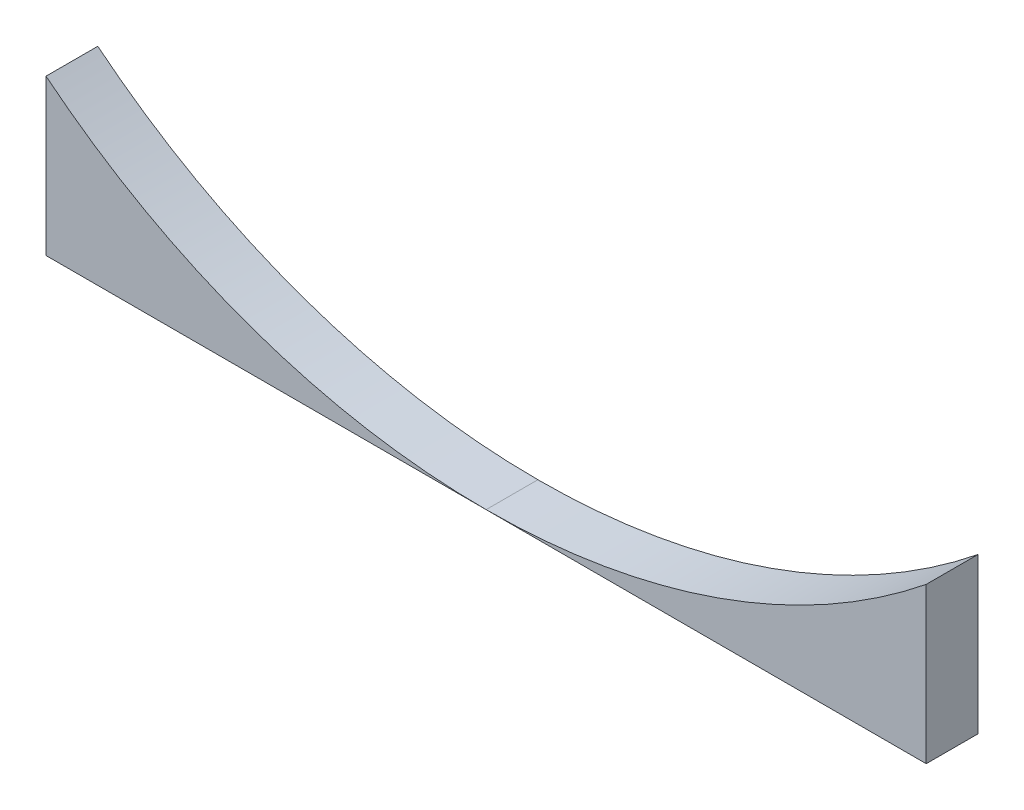
SolidWorks part; units mm, degrees
ref_plane "Front Plane" through (0, 0, 0) normal (0, 0, 1) x (1, 0, 0)
ref_plane "Top Plane" through (0, 0, 0) normal (0, 1, 0) x (1, 0, 0)
ref_plane "Right Plane" through (0, 0, 0) normal (1, 0, 0) x (0, 0, -1)
sketch "Sketch1" plane through (0, 0, 0) normal (0, 0, 1) x (1, 0, 0)
  line L0 (-170, 170.1445) -> (-170, 110.1445)
  line L1 (-170, 110.1445) -> (170, 110.1445)
  line L2 (170, 170.1445) -> (170, 110.1445)
  line L3 (-170, 410.1445) -> (170, 410.1445)
  line L4 (-170, 410.1445) -> (-170, 170.1445)
  line L5 (170, 410.1445) -> (170, 170.1445)
  line L6 (-170, 170.1445) -> (170, 170.1445) construction
  circle A0 centre (0, 270.1445) radius 5
  arc A1 (-170, 170.1445) -> (170, 170.1445) centre (0, 380.9778) ccw
  point P10 (0, 410.1445)
  point P18 (0, 170.1445)
  dimension "D4" = 10
  dimension "D1" = 60
  dimension "D5" = 340
  dimension "D6" = 240
  dimension "D7" = 240
  dimension "D8" = 140
extrude "Boss-Extrude1" add sketch "Sketch1" along normal blind 20 contours A1 L0 L1 | A1 L1 L2
